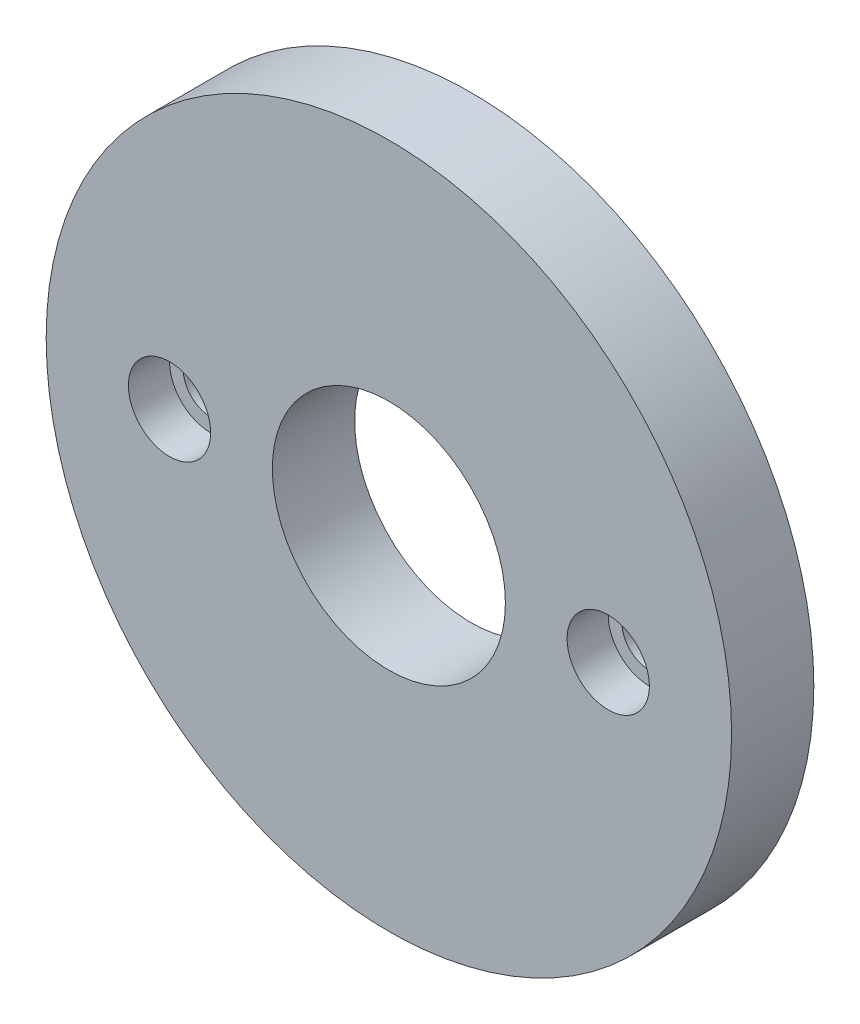
SolidWorks part; units mm, degrees
ref_plane "Plan de face" through (0, 0, 0) normal (0, 0, 1) x (1, 0, 0)
ref_plane "Plan de dessus" through (0, 0, 0) normal (0, 1, 0) x (1, 0, 0)
ref_plane "Plan de droite" through (0, 0, 0) normal (1, 0, 0) x (0, 0, -1)
sketch "Esquisse1" plane through (0, 0, 0) normal (0, 0, 1) x (1, 0, 0)
  circle A0 centre (0, 0) radius 8.5
  circle A1 centre (0, 0) radius 25
  dimension "D1" = 17
  dimension "D2" = 50
extrude "Boss.-Extru.3" add sketch "Esquisse1" along normal blind 6
sketch "Esquisse6" plane through (0, 0, 6) normal (0, 0, 1) x (1, 0, 0)
  line L0 (0, 25) -> (0, -25) construction
  line L1 (-25, 0) -> (25, 0) construction
  circle A0 centre (0, 0) radius 25 construction
  circle A1 centre (-16, 0) radius 3
  circle A2 centre (16, 0) radius 3
  dimension "D1" = 6
  dimension "D2" = 16
extrude "Enlèv. mat.-Extru.7" cut sketch "Esquisse6" against normal blind 3
sketch "Esquisse7" plane through (0, 0, 6) normal (0, 0, 1) x (1, 0, 0)
  circle A0 centre (-16, 0) radius 2
  circle A1 centre (16, 0) radius 2
  dimension "D1" = 4
  dimension "D2" = 4
extrude "Enlèv. mat.-Extru.8" cut sketch "Esquisse7" against normal blind 91
